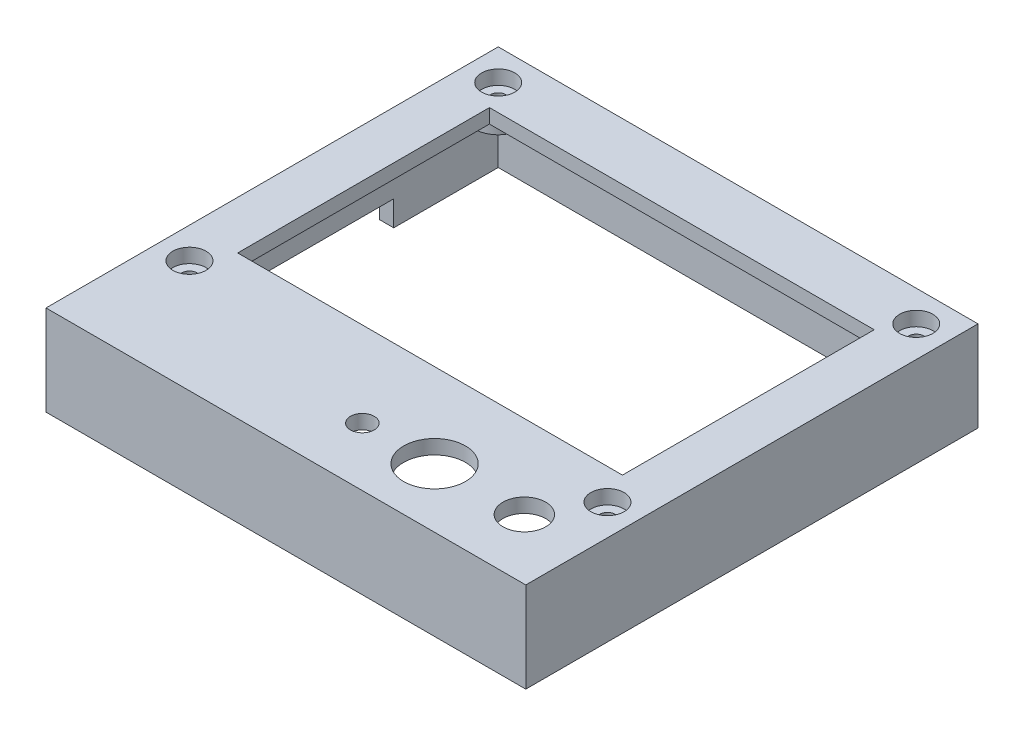
SolidWorks part; units mm, degrees
ref_plane "Front Plane" through (0, 0, 0) normal (0, 0, 1) x (1, 0, 0)
ref_plane "Top Plane" through (0, 0, 0) normal (0, 1, 0) x (1, 0, 0)
ref_plane "Right Plane" through (0, 0, 0) normal (1, 0, 0) x (0, 0, -1)
sketch "Sketch1" plane through (0, 0, 0) normal (0, 1, 0) x (1, 0, 0)
  line L0 (5.75, -5.75) -> (-93.25, -5.75) construction
  line L1 (0, 0) -> (-87.5, 0) construction
  line L2 (0, 0) -> (0, 81.7) construction
  line L3 (0, 81.7) -> (-87.5, 81.7) construction
  line L4 (-87.5, 0) -> (-87.5, 81.7) construction
  line L5 (-93.25, -5.75) -> (-93.25, 87.45) construction
  line L6 (5.75, 87.45) -> (-93.25, 87.45) construction
  line L7 (5.75, -5.75) -> (5.75, 87.45) construction
  line L8 (6.75, -6.75) -> (-94.25, -6.75)
  line L9 (-94.25, -6.75) -> (-94.25, 88.45)
  line L10 (6.75, 88.45) -> (-94.25, 88.45)
  line L11 (6.75, -6.75) -> (6.75, 88.45)
  dimension "D1" = 93.2
  dimension "D2" = 87.5
  dimension "D3" = 99
  dimension "D4" = 1
extrude "Boss-Extrude1" add sketch "Sketch1" along normal blind 19
shell "Shell1" thickness 3
sketch "Sketch8" plane through (0, 19, 0) normal (0, 1, 0) x (1, 0, 0)
  line L8 (7.75, -7.75) -> (7.75, 89.45)
  line L9 (7.75, -7.75) -> (7.75, 89.45)
  line L10 (7.75, 89.45) -> (-95.25, 89.45)
  line L11 (7.75, 89.45) -> (-95.25, 89.45)
  line L16 (-95.25, 89.45) -> (-95.25, -7.75)
  line L17 (-95.25, 89.45) -> (-95.25, -7.75)
  line L18 (-95.25, -7.75) -> (7.75, -7.75)
  line L19 (-95.25, -7.75) -> (7.75, -7.75)
  dimension "D1" = 1
sketch "Sketch2" plane through (0, 19, 0) normal (0, 1, 0) x (1, 0, 0)
  line L0 (-94.25, -6.75) -> (6.75, -6.75) construction
  line L1 (-83.45, 49.95) -> (-3.75, 49.95) construction
  line L2 (-84.1, 76.45) -> (-3.1, 76.45)
  line L3 (-84.1, 76.45) -> (-84.1, 23.45)
  line L4 (-84.1, 23.45) -> (-3.1, 23.45)
  line L5 (-3.1, 76.45) -> (-3.1, 23.45)
  line L6 (-84.1, 76.45) -> (-3.1, 23.45) construction
  line L7 (-84.1, 23.45) -> (-3.1, 76.45) construction
  line L9 (-87.75, 16.95) -> (-87.75, 81.95) construction
  line L10 (-87.75, 81.95) -> (0.25, 81.95) construction
  line L11 (0.25, 81.95) -> (0.25, 16.95) construction
  line L12 (0.25, 16.95) -> (-87.75, 16.95) construction
  line L14 (6.75, 88.45) -> (-94.25, 88.45) construction
  line L15 (-94.25, 88.45) -> (-94.25, -6.75) construction
  circle A0 centre (-87.75, 81.95) radius 3.5
  circle A1 centre (0.25, 81.95) radius 3.5
  circle A2 centre (-87.75, 16.95) radius 3.5
  circle A3 centre (0.25, 16.95) radius 3.5
  circle A4 centre (-6.25, 5.95) radius 4.5
  circle A5 centre (-24.95, 5.75) radius 6.5
  circle A6 centre (-39.95, 5.55) radius 2.5
  point P16 (-43.6, 49.95)
  dimension "D1" = 9
  dimension "D2" = 13
  dimension "D3" = 5
  dimension "D8" = 7
  dimension "D13" = 11.4
  dimension "D14" = 54.3
  dimension "D15" = 12.5
  dimension "D16" = 15.0013
  dimension "D17" = 18.7011
  dimension "D18" = 11
  dimension "D4" = 81
  dimension "D5" = 53
  dimension "D6" = 38.5
  dimension "D7" = 10.15
  dimension "D9" = 6.5
  dimension "D10" = 6.5
  dimension "D11" = 65
  dimension "D12" = 88
sketch "Sketch3" plane through (0, 16, 0) normal (0, -1, 0) x (1, 0, 0)
  line L0 (1.25, -82.95) -> (1.25, -17.95) construction
  line L1 (1.25, -17.95) -> (-88.75, -17.95) construction
  line L2 (-88.75, -17.95) -> (-88.75, -82.95) construction
  line L3 (-88.75, -82.95) -> (1.25, -82.95) construction
  line L7 (7.75, 7.75) -> (7.75, -89.45) construction
  line L8 (7.75, -89.45) -> (-95.25, -89.45) construction
  line L9 (-94.25, -88.45) -> (-94.25, 6.75) construction
  circle A0 centre (1.25, -82.95) radius 5
  circle A1 centre (-88.75, -82.95) radius 5
  circle A2 centre (-88.75, -17.95) radius 5
  circle A3 centre (1.25, -17.95) radius 5
  dimension "D2" = 10
  dimension "D3" = 6.5
  dimension "D1" = 6.5
  dimension "D4" = 5.5
  dimension "D5" = 65
extrude "Boss-Extrude2" add sketch "Sketch3" along normal blind 4
sketch "Sketch4" plane through (0, 12, 0) normal (0, -1, 0) x (1, 0, 0)
  line L0 (0.25, -81.95) -> (0.25, -16.95) construction
  line L1 (0.25, -16.95) -> (-87.75, -16.95) construction
  line L2 (-87.75, -16.95) -> (-87.75, -81.95) construction
  line L3 (-87.75, -81.95) -> (0.25, -81.95) construction
  line L7 (6.75, 6.75) -> (6.75, -88.45) construction
  line L8 (6.75, -88.45) -> (-94.25, -88.45) construction
  circle A0 centre (0.25, -16.95) radius 1.6
  circle A1 centre (-87.75, -16.95) radius 1.6
  circle A2 centre (-87.75, -81.95) radius 1.6
  circle A3 centre (0.25, -81.95) radius 1.6
  dimension "D4" = 3.2
  dimension "D1" = 88
  dimension "D2" = 6.5
  dimension "D3" = 6.5
  dimension "D5" = 65
extrude "Cut-Extrude2" cut sketch "Sketch4" against normal blind 22
sketch "Sketch6" plane through (-94.25, 0, 0) normal (-1, 0, 0) x (0, 0, 1)
  line L0 (-49.2, 5.3) -> (-49.2, 0) construction
  line L3 (-34.95, 0) -> (-63.45, 0)
  line L4 (-34.95, 0) -> (-34.95, 5.3)
  line L5 (-34.95, 5.3) -> (-63.45, 5.3)
  line L6 (-63.45, 0) -> (-63.45, 5.3)
  line L7 (-34.95, 0) -> (-63.45, 5.3) construction
  line L8 (-34.95, 5.3) -> (-63.45, 0) construction
  line L9 (-88.45, 19) -> (-88.45, 0) construction
  line L10 (-88.45, 19) -> (6.75, 19) construction
  point P4 (-49.2, 2.65)
  dimension "D1" = 5.3
  dimension "D2" = 28.5
  dimension "D3" = 25
  dimension "D4" = 13.7
extrude "Cut-Extrude3" cut sketch "Sketch6" against normal blind 22
extrude "Cut-Extrude5" cut sketch "Sketch2" against normal blind 3
